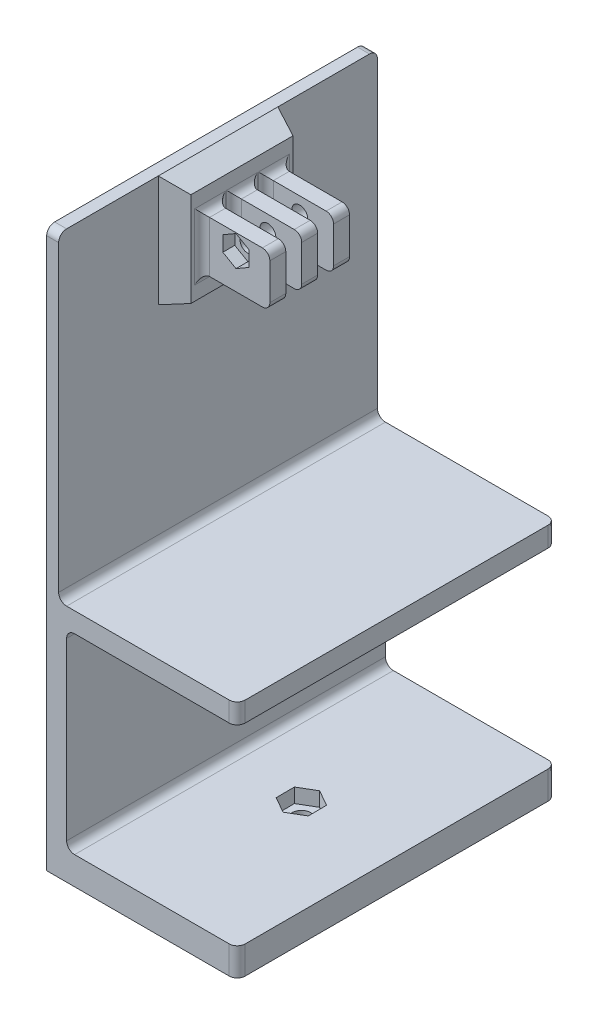
SolidWorks part; units mm, degrees
material "Rubber"
ref_plane "Front Plane" through (0, 0, 0) normal (0, 0, 1) x (1, 0, 0)
ref_plane "Top Plane" through (0, 0, 0) normal (0, 1, 0) x (1, 0, 0)
ref_plane "Right Plane" through (0, 0, 0) normal (1, 0, 0) x (0, 0, -1)
sketch "Sketch1" plane through (0, 0, 0) normal (0, 0, 1) x (1, 0, 0)
  line L0 (0, 0) -> (0, 76.2)
  line L1 (0, 76.2) -> (60.7194, 76.2)
  line L2 (60.7194, 76.2) -> (60.7194, 69.85)
  line L3 (60.7194, 69.85) -> (6.35, 69.85)
  line L4 (6.35, 69.85) -> (6.35, 8.89)
  line L5 (6.35, 8.89) -> (60.7194, 8.89)
  line L6 (60.7194, 8.89) -> (60.7194, 0)
  line L7 (60.7194, 0) -> (0, 0)
  dimension "D1" = 76.2
  dimension "D2" = 6.35
  dimension "D3" = 8.89
  dimension "D4" = 6.35
extrude "Boss-Extrude1" add sketch "Sketch1" along normal blind 101.6
sketch "Sketch2" plane through (0, 0, 0) normal (0, 1, 0) x (1, 0, 0)
  circle A0 centre (30.3597, -50.8) radius 2.9845
  dimension "D1" = 5.969
extrude "Cut-Extrude2" cut sketch "Sketch2" along normal up to next and the other way through all contours A0
sketch "Sketch8" plane through (0, 76.2, 0) normal (0, 1, 0) x (1, 0, 0)
  line L0 (60.7194, -101.6) -> (0, -101.6) construction
  line L1 (0, 0) -> (3.81, 0)
  line L2 (0, 0) -> (0, -101.6)
  line L3 (0, -101.6) -> (3.81, -101.6)
  line L4 (3.81, 0) -> (3.81, -101.6)
  dimension "D1" = 3.81
extrude "Boss-Extrude3" add sketch "Sketch8" along normal blind 101.6
sketch "Sketch20" plane through (0, 8.89, 0) normal (0, 1, 0) x (1, 0, 0)
  line L1 (35.4624, -53.6933) -> (35.4167, -47.8276)
  line L2 (35.4167, -47.8276) -> (30.314, -44.9343)
  line L3 (30.314, -44.9343) -> (25.257, -47.9067)
  line L4 (25.257, -47.9067) -> (25.3027, -53.7724)
  line L5 (25.3027, -53.7724) -> (30.4054, -56.6657)
  line L6 (30.4054, -56.6657) -> (35.4624, -53.6933)
  circle A0 centre (30.3597, -50.8) radius 5.08 construction
  dimension "D1" = 10.16
extrude "Cut-Extrude5" cut sketch "Sketch20" against normal blind 4.572
sketch "Sketch24" plane through (3.81, 0, 0) normal (1, 0, 0) x (0, 0, -1)
  line L0 (-101.6, 177.8) -> (0, 177.8) construction
  line L1 (-69.85, 177.8) -> (-31.75, 177.8)
  line L2 (-69.85, 177.8) -> (-69.85, 142.24)
  line L3 (-69.85, 142.24) -> (-31.75, 142.24)
  line L4 (-31.75, 177.8) -> (-31.75, 142.24)
  line L5 (-69.85, 177.8) -> (-31.75, 142.24) construction
  line L6 (-69.85, 142.24) -> (-31.75, 177.8) construction
  point P0 (-50.8, 160.02)
  point P9 (-50.8, 177.8)
  point P10 (-50.8, 177.8)
  dimension "D1" = 35.56
  dimension "D2" = 38.1
extrude "Boss-Extrude8" add sketch "Sketch24" along normal blind 7.62 draft 20 contours L2 L3 L4 L1
sketch "Sketch29" plane through (11.43, 0, 0) normal (1, 0, 0) x (0, 0, -1)
  line L0 (-67.0765, 175.0265) -> (-34.5235, 175.0265) construction
  line L1 (-63.5, 168.1745) -> (-58.42, 168.1745)
  line L2 (-63.5, 168.1745) -> (-63.5, 151.8655)
  line L3 (-63.5, 151.8655) -> (-58.42, 151.8655)
  line L4 (-58.42, 168.1745) -> (-58.42, 151.8655)
  line L5 (-53.34, 168.1745) -> (-48.26, 168.1745)
  line L6 (-53.34, 168.1745) -> (-53.34, 151.8655)
  line L7 (-53.34, 151.8655) -> (-48.26, 151.8655)
  line L8 (-48.26, 168.1745) -> (-48.26, 151.8655)
  line L9 (-43.18, 168.1745) -> (-38.1, 168.1745)
  line L10 (-43.18, 168.1745) -> (-43.18, 151.8655)
  line L11 (-43.18, 151.8655) -> (-38.1, 151.8655)
  line L12 (-38.1, 168.1745) -> (-38.1, 151.8655)
  line L15 (-34.5235, 175.0265) -> (-34.5235, 145.0135) construction
  line L16 (-34.5235, 175.0265) -> (-34.5235, 145.0135)
  point P14 (-50.8, 175.0265)
  point P15 (-50.8, 151.8655)
  point P17 (-34.5235, 160.02)
  point P18 (-43.18, 160.02)
  point P20 (-48.26, 160.02)
  point P21 (-58.42, 160.02)
  point P22 (-40.64, 168.1745)
  point P23 (-50.8, 168.1745)
  dimension "D1" = 5.08
  dimension "D2" = 5.08
  dimension "D3" = 5.08
  dimension "D4" = 5.08
  dimension "D5" = 5.08
extrude "Boss-Extrude10" add sketch "Sketch29" along normal blind 21.59 contours L10 L11 L12 L9 | L6 L7 L8 L5 | L2 L3 L4 L1
sketch "Sketch30" plane through (0, 0, 63.5) normal (0, 0, 1) x (1, 0, 0)
  line L1 (33.02, 170.2131) -> (33.02, 151.8655)
  line L2 (33.02, 151.8655) -> (11.43, 151.8655) construction
  line L3 (33.02, 151.8655) -> (11.43, 151.8655)
  line L4 (33.02, 168.1745) -> (11.43, 168.1745) construction
  circle A0 centre (22.225, 163.0945) radius 2.54
  point P8 (22.225, 151.8655)
  dimension "D1" = 5.08
  dimension "D2" = 5.08
extrude "Cut-Extrude8" cut sketch "Sketch30" against normal through all both and the other way through all contours A0
fillet "Fillet8" radius 2.38 18 edges at (11.43, 160.02, 43.18) (11.43, 151.8655, 40.64) (11.43, 160.02, 38.1) (11.43, 168.1745, 40.64) (11.43, 168.1745, 50.8) (11.43, 160.02, 48.26) (11.43, 160.02, 53.34) (11.43, 151.8655, 50.8) (11.43, 168.1745, 60.96) (11.43, 160.02, 58.42) (11.43, 151.8655, 60.96) (11.43, 160.02, 63.5) (33.02, 151.8655, 60.96) (33.02, 151.8655, 50.8) (33.02, 151.8655, 40.64) (33.02, 168.1745, 40.64) (33.02, 168.1745, 50.8) (33.02, 168.1745, 60.96)
sketch "Sketch31" plane through (0, 0, 63.5) normal (0, 0, 1) x (1, 0, 0)
  line L1 (26.416, 165.5142) -> (22.225, 167.9339)
  line L2 (22.225, 167.9339) -> (18.034, 165.5142)
  line L3 (18.034, 165.5142) -> (18.034, 160.6748)
  line L4 (18.034, 160.6748) -> (22.225, 158.2552)
  line L5 (22.225, 158.2552) -> (26.416, 160.6748)
  line L6 (26.416, 160.6748) -> (26.416, 165.5142)
  circle A0 centre (22.225, 163.0945) radius 4.191 construction
  point P1 (18.034, 163.0945)
  dimension "D1" = 8.382
extrude "Cut-Extrude9" cut sketch "Sketch31" against normal blind 3.81
fillet "Fillet9" radius 2.54 9 edges at (1.905, 177.8, 0) (1.905, 177.8, 101.6) (60.7194, 4.445, 0) (60.7194, 4.445, 101.6) (6.35, 8.89, 50.8) (6.35, 69.85, 50.8) (3.81, 76.2, 50.8) (60.7194, 73.025, 0) (60.7194, 73.025, 101.6)
